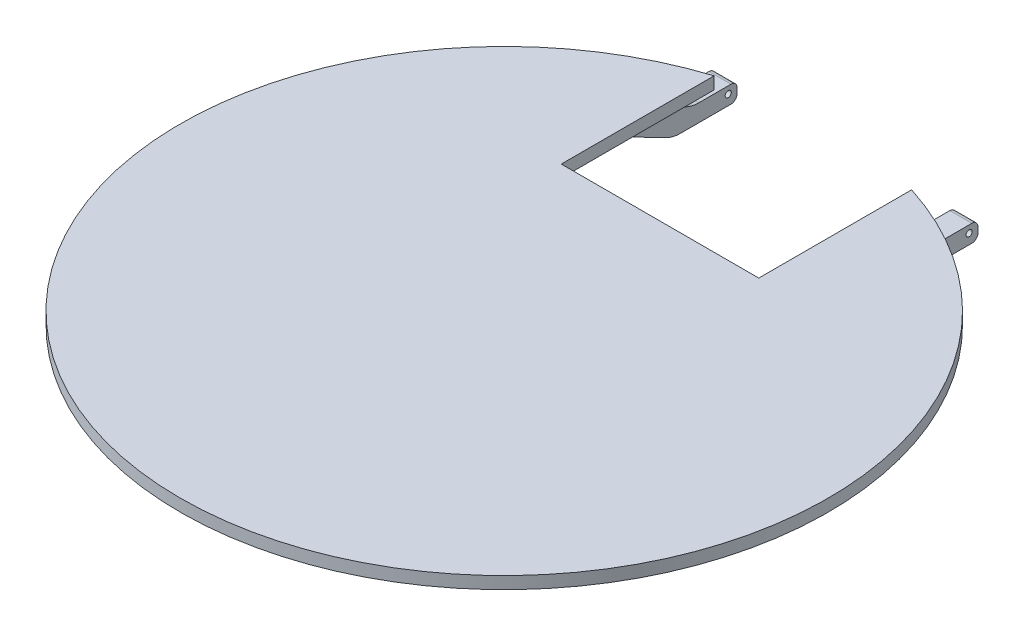
SolidWorks part; units mm, degrees
ref_plane "Piano frontale" through (0, 0, 0) normal (0, 0, 1) x (1, 0, 0)
ref_plane "Piano superiore" through (0, 0, 0) normal (0, 1, 0) x (1, 0, 0)
ref_plane "Piano destro" through (0, 0, 0) normal (1, 0, 0) x (0, 0, -1)
sketch "Schizzo1" plane through (0, 0, 0) normal (0, 1, 0) x (1, 0, 0)
  line L0 (0, -1000) -> (0, 49000) construction
  line L1 (0, 106) -> (32.3, 106)
  line L2 (32.3, 106) -> (32.3, 100.959)
  line L3 (0, 106) -> (-32.3, 106)
  line L4 (-32.3, 106) -> (-32.3, 100.959)
  line L5 (-32.3, 100.959) -> (-32.3, 50.959)
  line L6 (-32.3, 50.959) -> (32.3, 50.959)
  line L7 (32.3, 50.959) -> (32.3, 100.959)
  arc A0 (-32.3, 100.959) -> (32.3, 100.959) centre (0, 0) ccw
extrude "Estrusione-Estrusione1" add sketch "Schizzo1" along normal blind 4 contours L0 A0 L7 L6 | A0 L0 L6 L5
sketch "Schizzo2" plane through (0, 0, 0) normal (0, -1, 0) x (1, 0, 0)
  line L0 (32.3, -50.959) -> (35.8, -50.959) construction
  line L1 (35.8, -50.959) -> (35.8, -99.7715) construction
  line L2 (35.8, -99.7715) -> (35.8, -89.7715) construction
  line L4 (35.8, -89.7715) -> (43, -89.7715)
  line L5 (35.8, -89.7715) -> (35.8, -69.7715)
  line L6 (35.8, -69.7715) -> (43, -69.7715)
  line L7 (43, -89.7715) -> (43, -69.7715)
  arc A0 (32.3, -100.959) -> (-32.3, -100.959) centre (0, 0) ccw construction
ref_plane "Piano1" through (35.8, 0, 0) normal (-1, 0, 0) x (0, 0, 1)
sketch "Schizzo3" plane through (35.8, 0, 0) normal (-1, 0, 0) x (0, 0, 1)
  line L0 (-100.959, 0) -> (-100.959, 4)
  line L1 (-100.959, 0) -> (-100.959, 4)
  line L2 (-100.959, 4) -> (106, 4)
  line L3 (-100.959, 4) -> (106, 4)
  line L4 (106, 4) -> (106, 0)
  line L5 (106, 4) -> (106, 0)
  line L6 (106, 0) -> (-100.959, 0)
  line L7 (106, 0) -> (-100.959, 0)
  line L8 (-100.959, 0) -> (-90.959, 0) construction
  line L9 (-100.959, 0) -> (-100.959, -7) construction
  line L10 (-100.959, -7) -> (-109.069, -7) construction
  line L11 (-90.959, 0) -> (-70.959, 0)
  line L12 (-70.959, 0) -> (-88.8039, -9.1917)
  line L13 (-93.383, -10.3017) -> (-109.9686, -10.3017)
  line L14 (-111.9686, -8.3017) -> (-111.9686, -6.634)
  line L15 (-109.9686, -4.634) -> (-99.4675, -4.634)
  line L16 (-91.6376, -0.8542) -> (-90.959, 0)
  circle A0 centre (-109.069, -7) radius 1
  arc A1 (-99.4675, -4.634) -> (-91.6376, -0.8542) centre (-99.4675, 5.366) ccw
  arc A2 (-88.8039, -9.1917) -> (-93.383, -10.3017) centre (-93.383, -0.3017) cw
  arc A3 (-109.9686, -10.3017) -> (-111.9686, -8.3017) centre (-109.9686, -8.3017) cw
  arc A4 (-111.9686, -6.634) -> (-109.9686, -4.634) centre (-109.9686, -6.634) cw
  dimension "D1" = 10
  dimension "D2" = 2
extrude "Estrusione-Estrusione2" add sketch "Schizzo3" against normal blind 7.2 separate body contours A4 L14 A3 L13 A2 L12 L7 L16 A1 L15 A0
pattern_linear "Ripetizione a L1" count 2 spacing 78.8 along (-1, 0, 0) of bodies 102
sketch "Schizzo4" plane through (0, 0, 0) normal (0, -1, 0) x (1, 0, 0)
  line L0 (0, 106) -> (0, 74) construction
  line L1 (0, 201000) -> (0, -249000) construction
  line L2 (106, 0) -> (68, 0) construction
  line L3 (0, 74) -> (68, 74) construction
  line L4 (68, 74) -> (68, -41)
  line L5 (68, -41) -> (-97.7497, -41)
  line L6 (68, 74) -> (-75.8947, 74)
  line L7 (32.3, -100.959) -> (32.3, -50.959)
  line L8 (32.3, -100.959) -> (32.3, -50.959)
  line L9 (32.3, -50.959) -> (-32.3, -50.959)
  line L10 (32.3, -50.959) -> (-32.3, -50.959)
  line L11 (-32.3, -50.959) -> (-32.3, -100.959)
  line L12 (-32.3, -50.959) -> (-32.3, -100.959)
  arc A0 (32.3, -100.959) -> (-32.3, -100.959) centre (0, 0) ccw construction
  arc A1 (32.3, -100.959) -> (-32.3, -100.959) centre (0, 0) ccw
  arc A2 (32.3, -100.959) -> (-32.3, -100.959) centre (0, 0) ccw
  arc M7 (32.3, -100.959) -> (-32.3, -100.959) centre (0, 0) ccw
extrude "Taglio-Estrusione1" cut sketch "Schizzo4" against normal blind 0.0001 contours L4 L6 L5 M7
